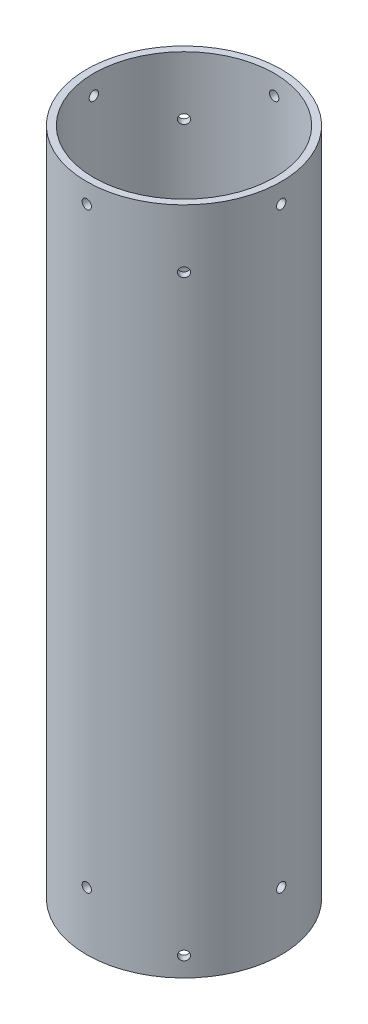
SolidWorks part; units mm, degrees
material "ПВХ 0.007 Смягченный"
ref_plane "Спереди" through (0, 0, 0) normal (0, 0, 1) x (1, 0, 0)
ref_plane "Сверху" through (0, 0, 0) normal (0, 1, 0) x (1, 0, 0)
ref_plane "Справа" through (0, 0, 0) normal (1, 0, 0) x (0, 0, -1)
sketch "Эскиз1" plane through (0, 0, 0) normal (0, 1, 0) x (1, 0, 0)
  circle A0 centre (0, 0) radius 25
  circle A1 centre (0, 0) radius 23.2
  dimension "ExDBody" = 50
  dimension "InDBody" = 46.4
extrude "Бобышка-Вытянуть1" add sketch "Эскиз1" along normal blind 172
ref_plane "Плоскость1" through (0, 31, 0) normal (0, -1, 0) x (-1, 0, 0)
sketch "Эскиз3" plane through (0, 0, 0) normal (1, 0, 0) x (0, 0, -1)
  line L0 (23.2, 172) -> (-23.2, 172) construction
  line L2 (-25, 0) -> (25, 0) construction
  circle A0 centre (0, 167) radius 1.2
  circle A3 centre (0, 15) radius 1.2
  dimension "D1" = 5
  dimension "D3" = 15
  dimension "D2" = 2.4
  dimension "D4" = 2.4
extrude "Вырез-Вытянуть2" cut sketch "Эскиз3" against normal through all
pattern_circular "Круговой массив1" count 4 over 360 about axis through (0, 172, 0) along (0, -1, 0) of "Вырез-Вытянуть2"
ref_plane "Плоскость2" through (0, 0, 0) normal (-0.7071, 0, 0.7071) x (0, -1, 0)
sketch "Эскиз11" plane through (0, 0, 0) normal (-0.7071, 0, 0.7071) x (0, -1, 0)
  line L0 (-172, 0) -> (0, 0) construction
  line L1 (0, -25) -> (0, 25) construction
  line L2 (-172, 25) -> (-172, -25) construction
  circle A0 centre (-5, 0) radius 1.2
  circle A1 centre (-157, 0) radius 1.2
  dimension "D1" = 2.4
  dimension "D3" = 15
  dimension "D4" = 2.4
  dimension "D2" = 5
extrude "Вырез-Вытянуть10" cut sketch "Эскиз11" against normal through all
pattern_circular "Круговой массив2" count 4 over 360 about axis through (0, 172, 0) along (0, -1, 0) of "Вырез-Вытянуть10"
